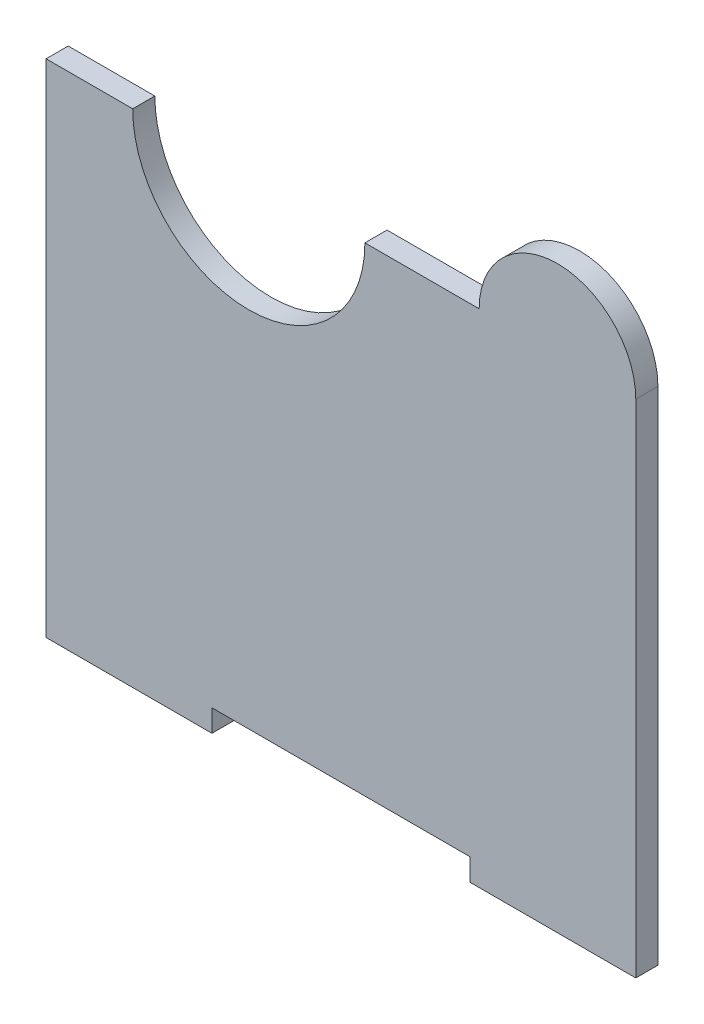
SolidWorks part; units mm, degrees
ref_plane "Front Plane" through (0, 0, 0) normal (0, 0, 1) x (1, 0, 0)
ref_plane "Top Plane" through (0, 0, 0) normal (0, 1, 0) x (1, 0, 0)
ref_plane "Right Plane" through (0, 0, 0) normal (1, 0, 0) x (0, 0, -1)
sketch "Sketch1" plane through (0, 0, 0) normal (0, 0, 1) x (1, 0, 0)
  line L0 (-55, 0) -> (-31.5, 0)
  line L2 (105, 0) -> (105, -136)
  line L3 (60, -130) -> (-10, -130)
  line L7 (-55, -136) -> (-10, -136)
  line L8 (-10, -130) -> (-10, -136)
  line L15 (105, -136) -> (60, -136)
  line L16 (60, -130) -> (60, -136)
  line L17 (-55, 0) -> (-55, -136)
  line L18 (31.5, 0) -> (62.5, 0)
  arc A1 (105, 0) -> (62.5, 0) centre (83.75, 0) ccw
  arc A2 (-31.5, 0) -> (31.5, 0) centre (0, 0) ccw
  dimension "D3" = 63
  dimension "D2" = 105
  dimension "D4" = 45
  dimension "D5" = 6
  dimension "D7" = 6
  dimension "D8" = 45
extrude "Boss-Extrude1" add sketch "Sketch1" along normal blind 6
